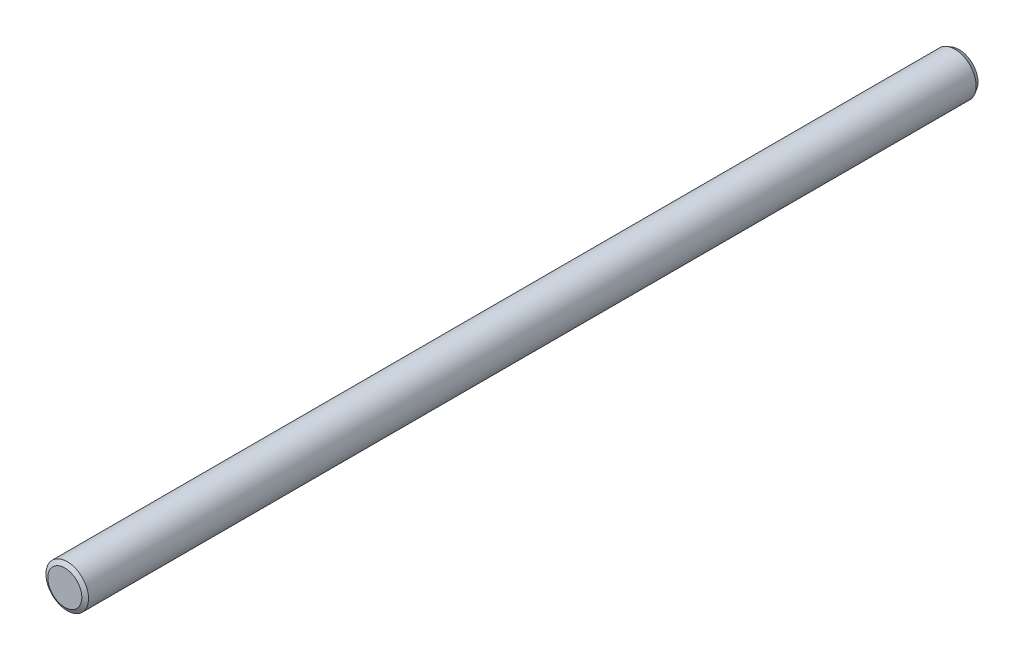
SolidWorks part; units mm, degrees
material "Liga de aço fundido"
ref_plane "Plano frontal" through (0, 0, 0) normal (0, 0, 1) x (1, 0, 0)
ref_plane "Plano superior" through (0, 0, 0) normal (0, 1, 0) x (1, 0, 0)
ref_plane "Plano direito" through (0, 0, 0) normal (1, 0, 0) x (0, 0, -1)
sketch "Esboço1" plane through (0, 0, 0) normal (0, 0, 1) x (1, 0, 0)
  circle A1 centre (0, 0) radius 2.5
  point P1 (0, 0)
  dimension "D1" = 5
extrude "Ressalto-extrusão1" add sketch "Esboço1" along normal blind 105
chamfer "Chanfro1" distance 0.5 angle 30 2 edges at (2.5, 0, 105) (2.5, 0, 0)
